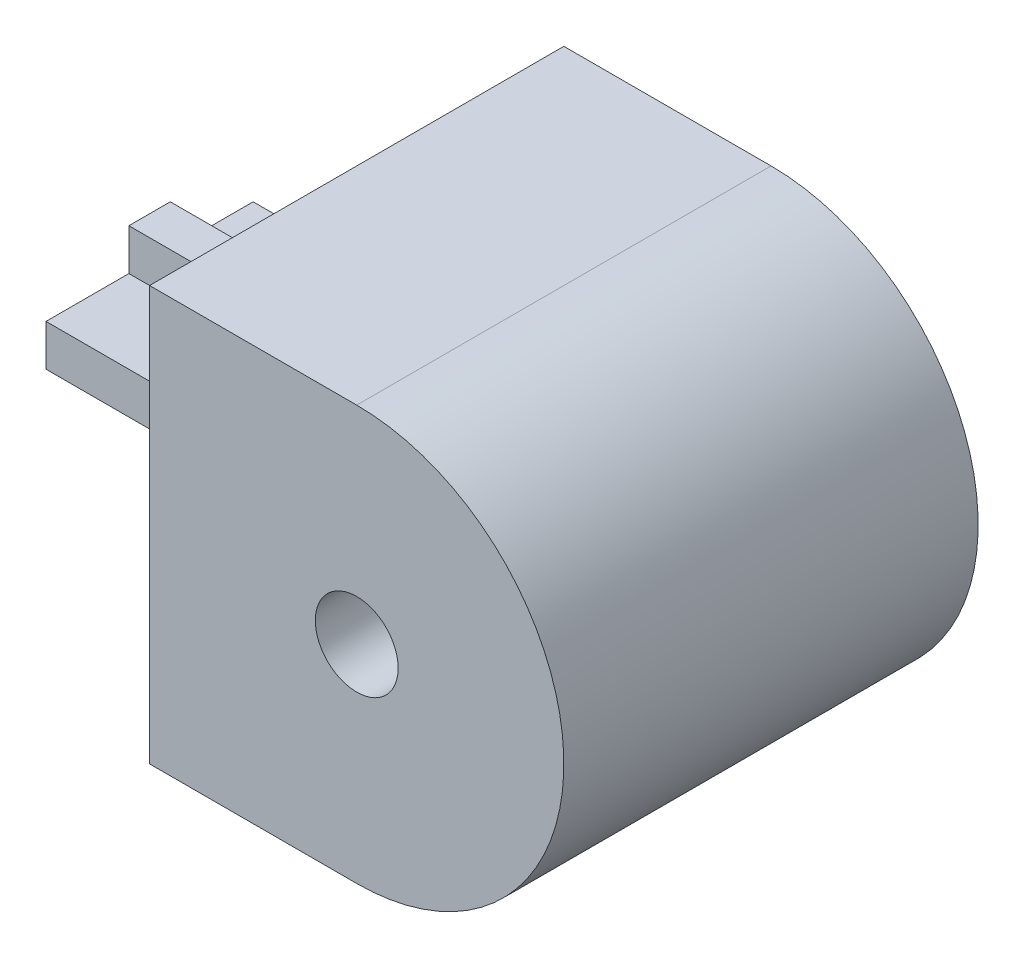
SolidWorks part; units mm, degrees
ref_plane "Front Plane" through (0, 0, 0) normal (0, 0, 1) x (1, 0, 0)
ref_plane "Top Plane" through (0, 0, 0) normal (0, 1, 0) x (1, 0, 0)
ref_plane "Right Plane" through (0, 0, 0) normal (1, 0, 0) x (0, 0, -1)
sketch "Sketch1" plane through (0, 0, 0) normal (0, 0, 1) x (1, 0, 0)
  line L0 (0, 5) -> (2.5, 5)
  line L1 (0, 0) -> (2.5, 0)
  line L2 (0, 5) -> (0, 0)
  arc A0 (2.5, 0) -> (2.5, 5) centre (2.5, 2.5) ccw
extrude "Boss-Extrude1" add sketch "Sketch1" along normal blind 5
sketch "Sketch2" plane through (0, 0, 0) normal (0, 0, 1) x (1, 0, 0)
  line L0 (2.5, 5) -> (2.5, 0) construction
  circle A0 centre (2.5, 2.5) radius 0.5
extrude "Cut-Extrude1" cut sketch "Sketch2" along normal through all
sketch "Sketch4" plane through (0, 0, 0) normal (-1, 0, 0) x (0, 0, 1)
  line L0 (2.25, 2.75) -> (2.25, 3.25)
  line L1 (2.25, 3.25) -> (2.75, 3.25)
  line L2 (2.75, 3.25) -> (2.75, 2.75)
  line L3 (2.75, 2.75) -> (3.75, 2.75)
  line L4 (3.75, 2.75) -> (3.75, 2.25)
  line L5 (3.75, 2.25) -> (2.75, 2.25)
  line L6 (2.75, 2.25) -> (2.75, 1.75)
  line L7 (2.75, 1.75) -> (2.25, 1.75)
  line L8 (2.25, 1.75) -> (2.25, 2.25)
  line L9 (2.25, 2.25) -> (1.25, 2.25)
  line L10 (1.25, 2.25) -> (1.25, 2.75)
  line L11 (1.25, 2.75) -> (2.25, 2.75)
  line L12 (1.25, 2.5) -> (3.75, 2.5) construction
  line L13 (2.5, 5) -> (2.5, 0) construction
  line L14 (5, 5) -> (0, 5) construction
  line L15 (5, 0) -> (0, 0) construction
  point P20 (2.5, 2.5)
  point P21 (2.5, 2.5)
  dimension "D1" = 1
  dimension "D2" = 0.5
  dimension "D3" = 0.5
extrude "Boss-Extrude2" add sketch "Sketch4" along normal blind 2.5
